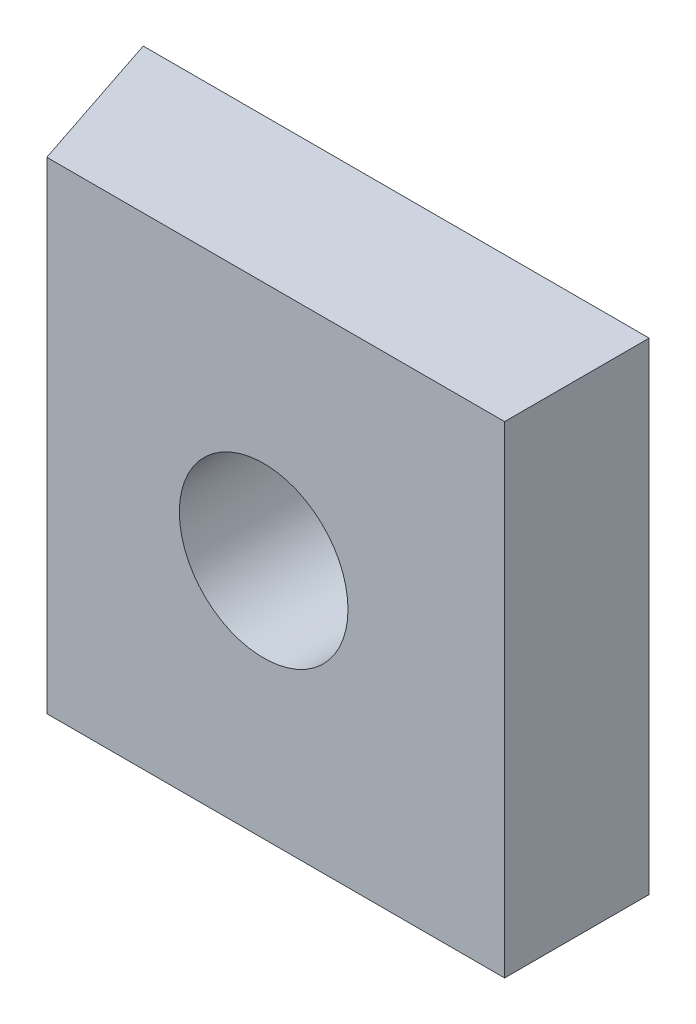
SolidWorks part; units mm, degrees
ref_plane "Front Plane" through (0, 0, 0) normal (0, 0, 1) x (1, 0, 0)
ref_plane "Top Plane" through (0, 0, 0) normal (0, 1, 0) x (1, 0, 0)
ref_plane "Right Plane" through (0, 0, 0) normal (1, 0, 0) x (0, 0, -1)
sketch "Sketch1" plane through (0, 0, 0) normal (0, 1, 0) x (1, 0, 0)
  line L0 (0, 0) -> (0, 3)
  line L1 (0, 3) -> (-10.5, 3)
  line L2 (-10.5, 3) -> (-9.5, 0)
  line L3 (-9.5, 0) -> (0, 0)
  dimension "D1" = 10.5
  dimension "D2" = 9.5
  dimension "D3" = 3
extrude "Boss-Extrude1" add sketch "Sketch1" along normal blind 10
sketch "Sketch2" plane through (0, 0, -3) normal (0, 0, -1) x (-1, 0, 0)
  line L0 (0, 5) -> (5, 5) construction
  line L1 (0, 10) -> (0, 0) construction
  circle A0 centre (5, 5) radius 1.75
  dimension "D2" = 3.5
  dimension "D1" = 5
extrude "Cut-Extrude1" cut sketch "Sketch2" against normal through all
